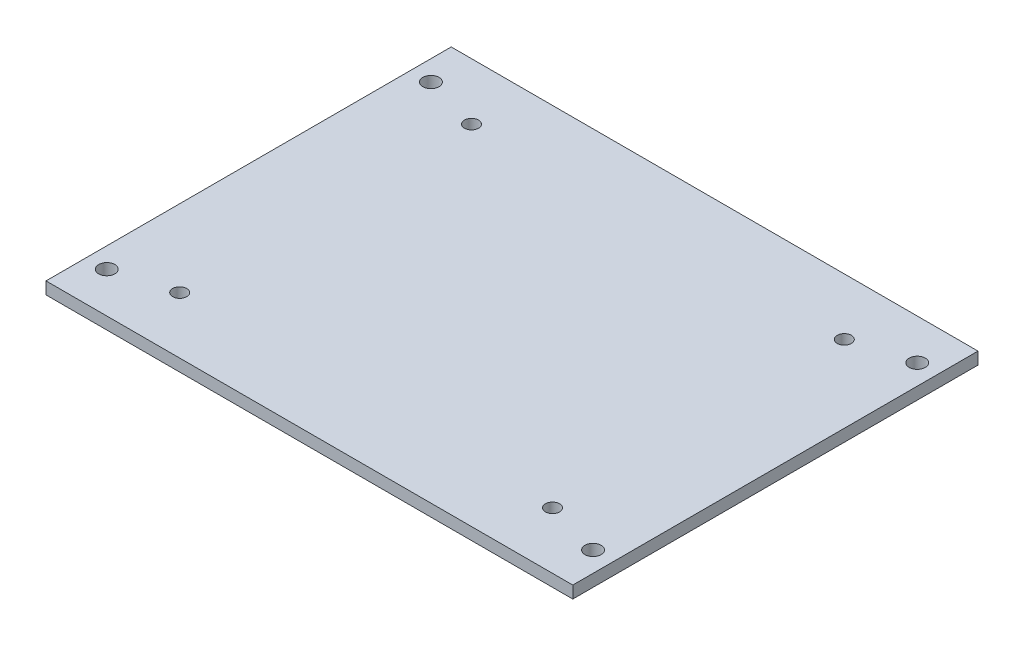
SolidWorks part; units mm, degrees
ref_plane "Plano frontal" through (0, 0, 0) normal (0, 0, 1) x (1, 0, 0)
ref_plane "Plano superior" through (0, 0, 0) normal (0, 1, 0) x (1, 0, 0)
ref_plane "Plano direito" through (0, 0, 0) normal (1, 0, 0) x (0, 0, -1)
sketch "Esboço2" plane through (0, 0, 0) normal (0, 1, 0) x (1, 0, 0)
  line L1 (-130, 100) -> (0, 100)
  line L2 (-130, 100) -> (-130, 0)
  line L3 (-130, 0) -> (0, 0)
  line L4 (0, 100) -> (0, 0)
extrude "Ressalto-extrusão1" add sketch "Esboço2" along normal blind 3
sketch "Esboço5" plane through (0, 3, 0) normal (0, 1, 0) x (1, 0, 0)
  line L0 (-111, 100) -> (-111, 0) construction
  line L1 (0, 100) -> (-130, 100) construction
  line L2 (-130, 0) -> (0, 0) construction
  line L3 (-130, 14) -> (0, 14) construction
  line L4 (-130, 100) -> (-130, 0) construction
  line L5 (0, 0) -> (0, 100) construction
  line L6 (-130, 86) -> (0, 86) construction
  line L7 (-19, 100) -> (-19, 0) construction
  circle A0 centre (-111, 86) radius 1.75
  circle A1 centre (-19, 86) radius 1.75
  circle A2 centre (-19, 14) radius 1.75
  circle A3 centre (-111, 14) radius 1.75
  dimension "D5" = 3.5
  dimension "D6" = 3.5
  dimension "D7" = 3.5
  dimension "D8" = 3.5
  dimension "D1" = 14
  dimension "D2" = 14
  dimension "D3" = 19
  dimension "D4" = 19
extrude "Corte-extrusão1" cut sketch "Esboço5" against normal blind 3
sketch "Esboço6" plane through (0, 3, 0) normal (0, 1, 0) x (1, 0, 0)
  circle A0 centre (-5, 90) radius 2
  circle A2 centre (-125, 90) radius 2
extrude "Corte-extrusão2" cut sketch "Esboço6" against normal blind 10 contours A0 | A2
sketch "Esboço7" plane through (0, 3, 0) normal (0, 1, 0) x (1, 0, 0)
  line L0 (-120.7534, 0) -> (-120.7534, 5) construction
  line L1 (-130, 0) -> (0, 0) construction
  line L2 (-130, 10) -> (-120, 10) construction
  line L3 (-130, 100) -> (-130, 0) construction
  line L4 (-125.2637, 5) -> (-125.2637, 15) construction
  circle A0 centre (-125, 10) radius 2
  dimension "D1" = 5
  dimension "D2" = 10
  dimension "D3" = 10
extrude "Corte-extrusão3" cut sketch "Esboço7" against normal blind 10
sketch "Esboço8" plane through (0, 3, 0) normal (0, 1, 0) x (1, 0, 0)
  circle A1 centre (-5, 10) radius 2
extrude "Corte-extrusão4" cut sketch "Esboço8" against normal blind 10
